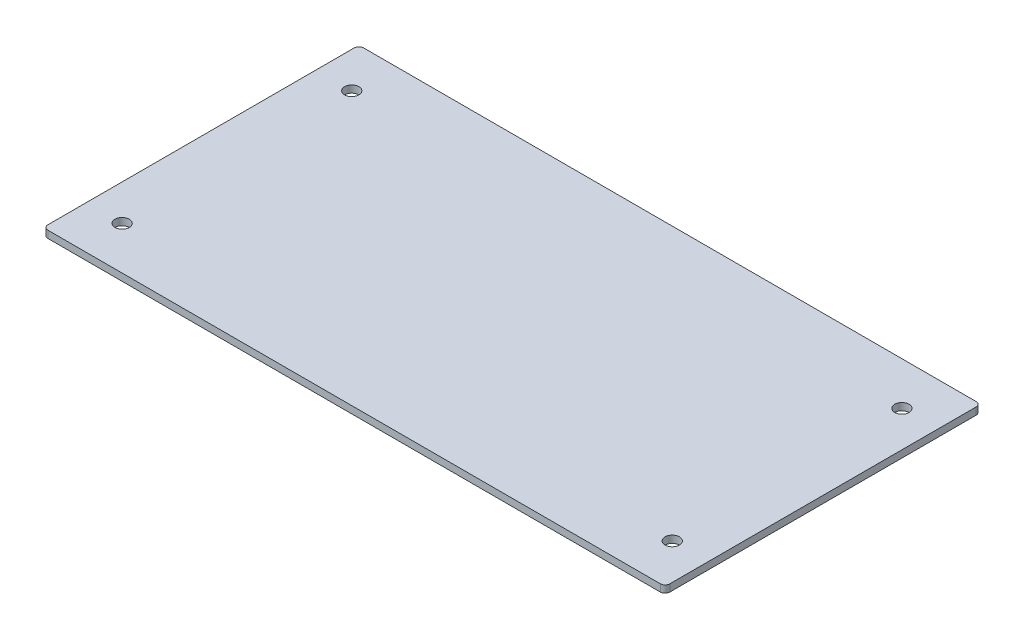
SolidWorks part; units mm, degrees
material "3.3535 (EN-AW 5754)"
ref_plane "Plan de face" through (0, 0, 0) normal (0, 0, 1) x (1, 0, 0)
ref_plane "Plan de dessus" through (0, 0, 0) normal (0, 1, 0) x (1, 0, 0)
ref_plane "Plan de droite" through (0, 0, 0) normal (1, 0, 0) x (0, 0, -1)
sketch "Esquisse1" plane through (0, 0, 0) normal (0, 1, 0) x (1, 0, 0)
  line L7 (65, -33) -> (-65, -33)
  line L8 (65, -33) -> (65, 33)
  line L9 (65, 33) -> (-65, 33)
  line L10 (-65, -33) -> (-65, 33)
  line L11 (0, 33) -> (0, -33) construction
  line L12 (65, 0) -> (-65, 0) construction
  circle A0 centre (57.5, 24) radius 1.5
  circle A1 centre (-57.5, 24) radius 1.5
  circle A2 centre (-57.5, -24) radius 1.5
  circle A3 centre (57.5, -24) radius 1.5
  point P5 (0, 0)
  dimension "D4" = 3
  dimension "D1" = 9
  dimension "D2" = 115
  dimension "D3" = 130
  dimension "D5" = 66
extrude "Boss.-Extru.1" add sketch "Esquisse1" along normal blind 1.5
fillet "Congé1" radius 1 4 edges at (65, 0.75, -33) (65, 0.75, 33) (-65, 0.75, 33) (-65, 0.75, -33)
